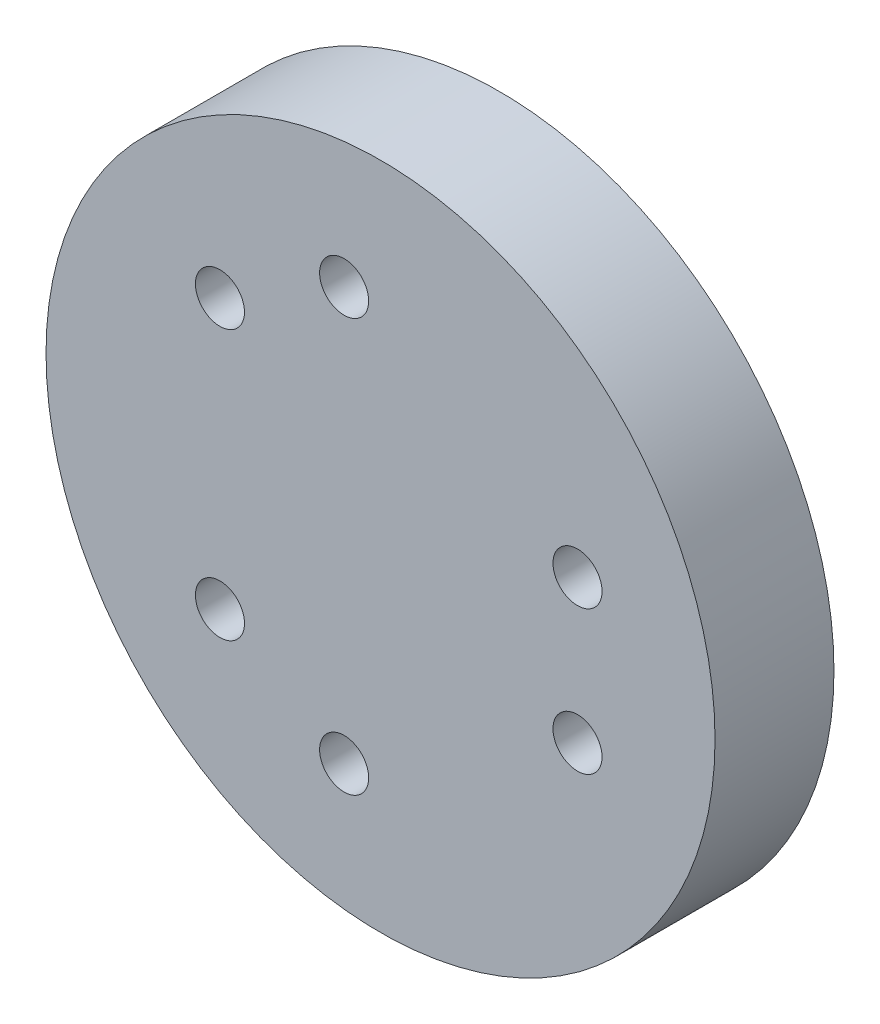
SolidWorks part; units mm, degrees
ref_plane "정면" through (0, 0, 0) normal (0, 0, 1) x (1, 0, 0)
ref_plane "윗면" through (0, 0, 0) normal (0, 1, 0) x (1, 0, 0)
ref_plane "우측면" through (0, 0, 0) normal (1, 0, 0) x (0, 0, -1)
sketch "스케치1" plane through (0, 0, 0) normal (0, 0, 1) x (1, 0, 0)
  line L0 (0, 0) -> (0, 22.5) construction
  line L1 (0, 0) -> (-3.9071, 22.1582) construction
  line L2 (0, 0) -> (-17.236, 14.4627) construction
  circle A0 centre (0, 0) radius 22.5
  circle A1 centre (0, 0) radius 14.1 construction
  circle A2 centre (-2.4484, 13.8858) radius 1.65
  circle A3 centre (-10.8012, 9.0633) radius 1.65
  circle A4 centre (13.2497, 4.8225) radius 1.65
  circle A5 centre (13.2497, -4.8225) radius 1.65
  circle A6 centre (-2.4484, -13.8858) radius 1.65
  circle A7 centre (-10.8012, -9.0633) radius 1.65
  point P22 (0, 0)
  dimension "D1" = 45
  dimension "D2" = 28.2
  dimension "D5" = 3.3
  dimension "D3" = 10
  dimension "D4" = 40
  dimension "D6" = 3
extrude "보스-돌출1" add sketch "스케치1" along normal blind 10
sketch "스케치3" plane through (0, 0, 0) normal (0, 0, -1) x (-1, 0, 0)
  circle A0 centre (2.4484, 13.8858) radius 3
  circle A1 centre (10.8012, 9.0633) radius 3
  circle A2 centre (10.8012, -9.0633) radius 3
  circle A3 centre (2.4484, -13.8858) radius 3
  circle A4 centre (-13.2497, -4.8225) radius 3
  circle A5 centre (-13.2497, 4.8225) radius 3
  dimension "D1" = 6
extrude "컷-돌출1" cut sketch "스케치3" against normal blind 7
sketch "스케치4" plane through (0, 0, 0) normal (0, 0, -1) x (-1, 0, 0)
  line L0 (0, 0) -> (10.8185, 6.2617) construction
  line L1 (0, 0) -> (10.8012, -6.0633) construction
  line L2 (0, 0) -> (12.0525, 3.3147) construction
  line L3 (0, 0) -> (12.0951, -3.1557) construction
  circle A1 centre (12.0525, 3.3147) radius 1.1
  circle A2 centre (10.8012, -9.0633) radius 3 construction
  circle A3 centre (12.0951, -3.1557) radius 1.1
  circle A4 centre (-3.1557, -12.0951) radius 1.1
  circle A5 centre (-8.7805, -8.8968) radius 1.1
  circle A6 centre (-8.8968, 8.7805) radius 1.1
  circle A7 centre (-3.3147, 12.0525) radius 1.1
  point P22 (0, 0)
  dimension "D1" = 14.685
  dimension "D5" = 2.2
  dimension "D6" = 2.2
  dimension "D2" = 30
  dimension "D3" = 14.685
  dimension "D4" = 3
extrude "컷-돌출2" cut sketch "스케치4" against normal blind 8
sketch "스케치5" plane through (0, 0, 0) normal (0, 0, -1) x (-1, 0, 0)
  circle A0 centre (0, 0) radius 22.5
  circle A1 centre (2.4484, 13.8858) radius 3
  circle A2 centre (10.8012, 9.0633) radius 3
  circle A3 centre (12.0525, 3.3147) radius 1.1
  circle A4 centre (12.0951, -3.1557) radius 1.1
  circle A5 centre (10.8012, -9.0633) radius 3
  circle A6 centre (2.4484, -13.8858) radius 3
  circle A7 centre (-3.1557, -12.0951) radius 1.1
  circle A8 centre (-8.7805, -8.8968) radius 1.1
  circle A9 centre (-13.2497, -4.8225) radius 3
  circle A10 centre (-13.2497, 4.8225) radius 3
  circle A11 centre (-8.8968, 8.7805) radius 1.1
  circle A12 centre (-3.3147, 12.0525) radius 1.1
  dimension "D1" = 2.2
  dimension "D2" = 2.2
extrude "컷-돌출3" cut sketch "스케치5" against normal blind 2
sketch "스케치6" plane through (0, 0, 2) normal (0, 0, -1) x (-1, 0, 0)
  line L0 (-22.5, 0) -> (22.5, 0) construction
  line L1 (0, 0) -> (5.6, 0) construction
  line L2 (0, 0) -> (-5.6, 0) construction
  line L3 (0, 0) -> (0, 5.6) construction
  line L4 (0, 0) -> (0, -5.6) construction
  circle A0 centre (0, 0) radius 22.5 construction
  circle A3 centre (0, 5.6) radius 1
  circle A4 centre (0, -5.6) radius 1
  dimension "D1" = 5.6
  dimension "D3" = 2
  dimension "D2" = 5.6
extrude "컷-돌출4" cut sketch "스케치6" against normal blind 2
